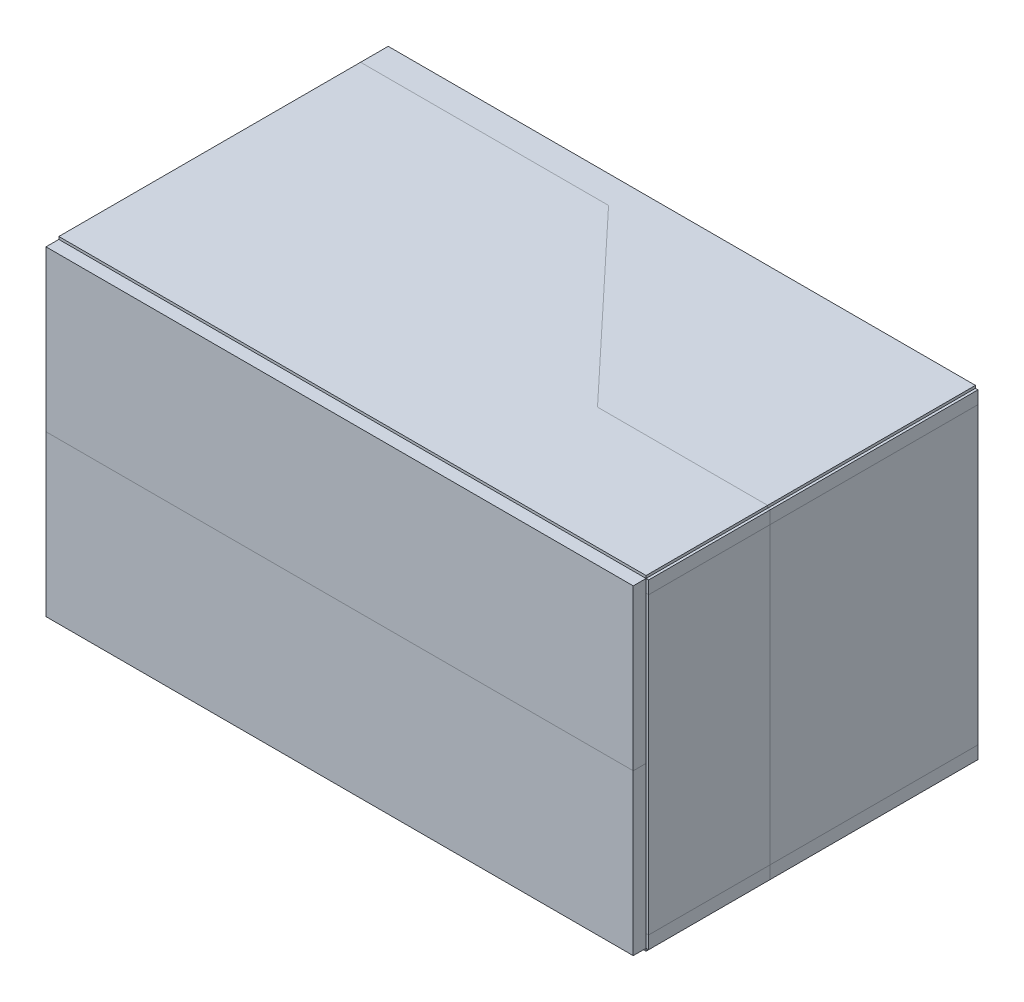
SolidWorks part; units mm, degrees
other "후면"
other "천장2"
other "천장1"
other "좌측면"
other "정면"
other "우측면"
other "바닥"
other "후면하단작음2"
other "후면상단작음2"
other "상단인테리어2"
other "하단인테리어2"
other "후면하단큼1"
other "후면상단큼1"
other "후면하단작음1"
other "후면상단작음1"
other "상단인테리어1"
other "하단인테리어1"
other "TV다이"
other "TV다이문1"
other "TV다이문2"
other "TV다이문3"
other "TV다이문4"
other "TV다이문고리1"
other "TV다이문고리2"
other "TV다이문고리3"
other "TV다이문고리4"
other "게임기1"
other "게임기2"
other "게임기2 버튼1"
other "게임기2 버튼2"
other "게임기2 버튼3"
other "게임기2 버튼4"
other "게임기2 버튼5"
other "게임기2 버튼6"
other "TV"
other "중간테이블"
other "소파"
other "에어컨"
other "카펫"
ref_plane "정면" through (0, 0, 0) normal (0, 0, 1) x (1, 0, 0)
ref_plane "윗면" through (0, 0, 0) normal (0, 1, 0) x (1, 0, 0)
ref_plane "우측면" through (0, 0, 0) normal (1, 0, 0) x (0, 0, -1)
sketch "스케치1" plane through (0, 0, 0) normal (0, 0, 1) x (1, 0, 0)
  line L1 (51, 74.896) -> (280, 74.896)
  line L2 (51, 74.896) -> (51, -50)
  line L3 (51, -50) -> (280, -50)
  line L4 (280, 74.896) -> (280, -50)
extrude "보스-돌출1" add sketch "스케치1" along normal up to surface (7.8606 mm away)
sketch "스케치2" plane through (0, 0, 7.8606) normal (0, 0, 1) x (1, 0, 0)
  line L0 (280, 74.896) -> (280, -50) construction
  line L1 (51, 74.896) -> (280, 74.896)
  line L2 (51, 74.896) -> (51, 69.896)
  line L3 (51, 69.896) -> (280, 69.896)
  line L4 (280, 74.896) -> (280, 69.896)
  dimension "D1" = 5
extrude "컷-돌출1" cut sketch "스케치2" against normal up to surface (7.8606 mm away) contours L1 L3 L2 up to face at (165.5, 12.448, 0)
sketch "스케치4" plane through (0, 0, 7.8606) normal (0, 0, 1) x (1, 0, 0)
  line L0 (280, 69.896) -> (280, -50) construction
  line L1 (51, -50) -> (280, -50)
  line L2 (51, -50) -> (51, -45)
  line L3 (51, -45) -> (280, -45)
  line L4 (280, -50) -> (280, -45)
  line M1 (280, -50) -> (280, 69.896)
  line M3 (51, 69.896) -> (51, -50)
  line M4 (51, -50) -> (280, -50)
  dimension "D1" = 5
extrude "컷-돌출2" cut sketch "스케치4" against normal up to surface (7.8606 mm away) contours L3 M3 M4 M1 up to face at (165.5, 9.948, 0)
sketch "스케치5" plane through (0, 0, 7.8606) normal (0, 0, 1) x (1, 0, 0)
  line L0 (51, -45) -> (280, -45) construction
  line L1 (280, 69.896) -> (275, 69.896)
  line L2 (280, 69.896) -> (280, -45)
  line L3 (280, -45) -> (275, -45)
  line L4 (275, 69.896) -> (275, -45)
  line M1 (51, -45) -> (280, -45)
  line M2 (280, -45) -> (280, 69.896)
  line M3 (280, 69.896) -> (51, 69.896)
  dimension "D1" = 5
extrude "컷-돌출3" cut sketch "스케치5" against normal up to surface (7.8606 mm away) contours L4 M3 M1 M2 up to face at (165.5, 12.448, 0)
sketch "스케치6" plane through (0, 69.896, 0) normal (0, 1, 0) x (1, 0, 0)
  line L1 (51, 0) -> (280, 0)
  line L2 (51, 0) -> (51, -128.4421)
  line L3 (51, -128.4421) -> (280, -128.4421)
  line L4 (280, 0) -> (280, -128.4421)
extrude "보스-돌출3" add sketch "스케치6" along normal blind 5 separate body
sketch "스케치7" plane through (0, 0, 7.8606) normal (0, 0, 1) x (1, 0, 0)
  line L0 (51, -45) -> (275, -45) construction
  line L1 (51, 69.896) -> (56, 69.896)
  line L2 (51, 69.896) -> (51, -45)
  line L3 (51, -45) -> (56, -45)
  line L4 (56, 69.896) -> (56, -45)
  dimension "D1" = 5
extrude "보스-돌출4" add sketch "스케치7" along normal up to surface (120.5815 mm away) separate body up to face at (165.5, 72.396, 128.4421)
sketch "스케치8" plane through (0, -45, 0) normal (0, -1, 0) x (1, 0, 0)
  line L1 (51, 128.4421) -> (280, 128.4421)
  line L2 (51, 128.4421) -> (51, 0)
  line L3 (51, 0) -> (280, 0)
  line L4 (280, 128.4421) -> (280, 0)
extrude "보스-돌출5" add sketch "스케치8" along normal blind 5 separate body
sketch "스케치9" plane through (0, 0, 128.4421) normal (0, 0, 1) x (1, 0, 0)
  line L1 (51, 74.896) -> (280, 74.896)
  line L2 (51, 74.896) -> (51, 12.446)
  line L3 (51, 12.446) -> (280, 12.446)
  line L4 (280, 74.896) -> (280, 12.446)
  dimension "D1" = 62.45
extrude "보스-돌출6" add sketch "스케치9" along normal blind 5 separate body
sketch "스케치10" plane through (0, 0, 128.4421) normal (0, 0, 1) x (1, 0, 0)
  line L1 (51, 12.446) -> (280, 12.446)
  line L2 (51, 12.446) -> (51, -50)
  line L3 (51, -50) -> (280, -50)
  line L4 (280, 12.446) -> (280, -50)
extrude "보스-돌출7" add sketch "스케치10" along normal blind 5 separate body
sketch "스케치11" plane through (275, 0, 0) normal (1, 0, 0) x (0, 0, -1)
  line L1 (0, -45) -> (-128.4421, -45)
  line L2 (0, -45) -> (0, 69.896)
  line L3 (0, 69.896) -> (-128.4421, 69.896)
  line L4 (-128.4421, -45) -> (-128.4421, 69.896)
extrude "보스-돌출8" add sketch "스케치11" along normal blind 5 separate body
sketch "스케치12" plane through (0, -50, 0) normal (0, -1, 0) x (1, 0, 0)
  line L0 (51, 10.7712) -> (147.7059, 10.7712)
  line L1 (51, 128.4421) -> (51, 0) construction
  line L2 (147.7059, 10.7712) -> (213.6585, 81.0356)
  line L3 (213.6585, 81.0356) -> (280, 81.0356)
  line L4 (280, 0) -> (280, 128.4421) construction
  line L5 (51, 10.7712) -> (51, 0)
  line L6 (51, 0) -> (280, 0)
  line L7 (280, 0) -> (280, 81.0356)
extrude "보스-돌출9" add sketch "스케치12" along normal blind 1 separate body
sketch "스케치13" plane through (0, -50, 0) normal (0, -1, 0) x (1, 0, 0)
  line L0 (51, 128.4421) -> (51, 10.7712)
  line L1 (51, 10.7712) -> (147.7059, 10.7712)
  line L2 (147.7059, 10.7712) -> (213.6585, 81.0356)
  line L3 (213.6585, 81.0356) -> (280, 81.0356)
  line L4 (280, 81.0356) -> (280, 128.4421)
  line L5 (280, 128.4421) -> (51, 128.4421)
extrude "보스-돌출10" add sketch "스케치13" along normal blind 1 separate body
sketch "스케치14" plane through (280, 0, 0) normal (1, 0, 0) x (0, 0, -1)
  line L1 (-81.0356, -50) -> (-128.4421, -50)
  line L2 (-81.0356, -50) -> (-81.0356, -45)
  line L3 (-81.0356, -45) -> (-128.4421, -45)
  line L4 (-128.4421, -50) -> (-128.4421, -45)
extrude "보스-돌출11" add sketch "스케치14" along normal blind 1 separate body
sketch "스케치15" plane through (280, 0, 0) normal (1, 0, 0) x (0, 0, -1)
  line L1 (-81.0356, -50) -> (0, -50)
  line L2 (-81.0356, -50) -> (-81.0356, -45)
  line L3 (-81.0356, -45) -> (0, -45)
  line L4 (0, -50) -> (0, -45)
extrude "보스-돌출12" add sketch "스케치15" along normal blind 1 separate body
sketch "스케치16" plane through (280, 0, 0) normal (1, 0, 0) x (0, 0, -1)
  line L0 (-128.4421, 69.896) -> (0, 69.896) construction
  line L1 (-128.4421, -45) -> (-81.0356, -45)
  line L2 (-128.4421, -45) -> (-128.4421, 69.896)
  line L3 (-128.4421, 69.896) -> (-81.0356, 69.896)
  line L4 (-81.0356, -45) -> (-81.0356, 69.896)
extrude "보스-돌출13" add sketch "스케치16" along normal blind 1 separate body
sketch "스케치17" plane through (280, 0, 0) normal (1, 0, 0) x (0, 0, -1)
  line L0 (0, 74.896) -> (0, 69.896) construction
  line L1 (-81.0356, -45) -> (0, -45)
  line L2 (-81.0356, -45) -> (-81.0356, 69.896)
  line L3 (-81.0356, 69.896) -> (0, 69.896)
  line L4 (0, -45) -> (0, 69.896)
  line L5 (-128.4421, 69.896) -> (0, 69.896) construction
extrude "보스-돌출14" add sketch "스케치17" along normal blind 1 separate body
ref_plane "평면1" through (0, 12.446, 0) normal (0, 1, 0) x (1, 0, 0)
mirror "대칭 복사2" about plane through (0, 12.446, 0) normal (0, 1, 0) of bodies 112 113 114 115
other "바디 저장1"
other "바디 저장2"
sketch "스케치18" plane through (0, 0, 7.8606) normal (0, 0, 1) x (1, 0, 0)
  line L0 (51, 69.896) -> (280, 69.896) construction
  line L1 (105.5, 69.896) -> (225.5, 69.896)
  line L2 (105.5, 69.896) -> (105.5, 49.896)
  line L3 (105.5, 49.896) -> (225.5, 49.896)
  line L4 (225.5, 69.896) -> (225.5, 49.896)
  line L5 (56, 69.896) -> (56, -45) construction
  dimension "D1" = 120
  dimension "D2" = 49.5
  dimension "D3" = 20
extrude "보스-돌출15" add sketch "스케치18" along normal blind 30 separate body
sketch "스케치19" plane through (0, 49.896, 0) normal (0, -1, 0) x (1, 0, 0)
  line L0 (105.5, 37.8606) -> (105.5, 7.8606) construction
  line L1 (105.5, 32.8606) -> (225.5, 32.8606)
  line L2 (105.5, 32.8606) -> (105.5, 12.8606)
  line L3 (105.5, 12.8606) -> (225.5, 12.8606)
  line L4 (225.5, 32.8606) -> (225.5, 12.8606)
  line L5 (225.5, 37.8606) -> (225.5, 7.8606) construction
  line L6 (105.5, 37.8606) -> (225.5, 37.8606) construction
  dimension "D1" = 5
  dimension "D2" = 20
extrude "컷-돌출4" cut sketch "스케치19" against normal blind 2
sketch "스케치20" plane through (0, 51.896, 0) normal (0, -1, 0) x (1, 0, 0)
  line L1 (105.5, 12.8606) -> (225.5, 12.8606) construction
  line L2 (105.5, 32.8606) -> (134.75, 32.8606)
  line L3 (105.5, 32.8606) -> (105.5, 12.8606)
  line L4 (105.5, 12.8606) -> (134.75, 12.8606)
  line L5 (134.75, 32.8606) -> (134.75, 12.8606)
  dimension "D1" = 29.25
extrude "보스-돌출16" add sketch "스케치20" along normal blind 2 separate body
pattern_linear "선형 패턴1" count 4 spacing 30.25 along (1, 0, 0) of bodies 160
sketch "스케치21" plane through (0, 49.896, 0) normal (0, -1, 0) x (1, 0, 0)
  line L0 (134.75, 32.8606) -> (105.5, 32.8606) construction
  line L1 (134.75, 12.8606) -> (134.75, 32.8606) construction
  line L2 (134.75, 32.8606) -> (135.75, 32.8606) construction
  line L3 (135.25, 32.8606) -> (135.25, 12.8606) construction
  line L4 (105.5, 12.8606) -> (225.5, 12.8606) construction
  line L5 (165, 32.8606) -> (166, 32.8606) construction
  line L6 (165.5, 32.8606) -> (165.5, 12.8606) construction
  line L7 (105.5, 12.8606) -> (225.5, 12.8606) construction
  line L8 (195.75, 32.8606) -> (195.75, 12.8606) construction
  line L9 (196.25, 32.8606) -> (195.25, 32.8606) construction
  circle A0 centre (131.75, 22.8606) radius 1
  circle A1 centre (138.75, 22.8606) radius 1
  circle A2 centre (192.25, 22.8606) radius 1
  circle A3 centre (199.25, 22.8606) radius 1
  dimension "D1" = 2
  dimension "D2" = 10
  dimension "D3" = 3
extrude "보스-돌출18" add sketch "스케치21" along normal blind 1 separate body
sketch "스케치23" plane through (0, 0, 37.8606) normal (0, 0, 1) x (1, 0, 0)
  line L0 (225.5, 69.896) -> (105.5, 69.896) construction
  line L1 (108.2391, 50.896) -> (114.2391, 50.896)
  line L2 (108.2391, 50.896) -> (108.2391, 65.896)
  line L3 (108.2391, 65.896) -> (114.2391, 65.896)
  line L4 (114.2391, 50.896) -> (114.2391, 65.896)
  dimension "D1" = 6
  dimension "D2" = 15
  dimension "D3" = 4
extrude "보스-돌출19" add sketch "스케치23" along normal blind 15 separate body
sketch "스케치24" plane through (0, 50.896, 0) normal (0, -1, 0) x (1, 0, 0)
  line L0 (108.2391, 52.8606) -> (114.2391, 52.8606) construction
  line L1 (108.7391, 52.8606) -> (113.7391, 52.8606)
  line L2 (108.7391, 52.8606) -> (108.7391, 37.8606)
  line L3 (108.7391, 37.8606) -> (113.7391, 37.8606)
  line L4 (113.7391, 52.8606) -> (113.7391, 37.8606)
  line L5 (108.2391, 37.8606) -> (114.2391, 37.8606) construction
  line L6 (108.2391, 52.8606) -> (108.2391, 37.8606) construction
  dimension "D1" = 5
  dimension "D2" = 0.5
extrude "컷-돌출5" cut sketch "스케치24" against normal blind 2
sketch "스케치25" plane through (0, 0, 52.8606) normal (0, 0, 1) x (1, 0, 0)
  line L0 (114.2391, 65.896) -> (108.2391, 65.896) construction
  line L1 (108.7391, 52.896) -> (113.7391, 52.896)
  line L2 (108.7391, 52.896) -> (108.7391, 64.896)
  line L3 (108.7391, 64.896) -> (113.7391, 64.896)
  line L4 (113.7391, 52.896) -> (113.7391, 64.896)
  dimension "D1" = 1
extrude "컷-돌출6" cut sketch "스케치25" against normal blind 2
sketch "스케치27" plane through (0, 50.896, 0) normal (0, -1, 0) x (1, 0, 0)
  line L9 (108.7391, 52.8606) -> (108.7391, 37.8606)
  line L10 (108.7391, 52.8606) -> (108.7391, 37.8606) construction
  line L11 (108.2391, 37.8606) -> (108.7391, 37.8606) construction
  line L12 (108.7391, 37.8606) -> (111.2391, 37.8606)
  line L13 (111.2391, 37.8606) -> (108.7391, 52.8606)
  dimension "D1" = 2.5
extrude "보스-돌출23" add sketch "스케치27" against normal up to surface (14 mm away) up to face at (111.2391, 64.896, 51.8606)
sketch "스케치28" plane through (0, 50.896, 0) normal (0, -1, 0) x (1, 0, 0)
  line L1 (113.7391, 37.8606) -> (113.7391, 52.8606)
  line L2 (113.7391, 52.8606) -> (114.2391, 52.8606) construction
  line L3 (113.7391, 52.8606) -> (108.7391, 52.8606) construction
  line L5 (113.7391, 37.8606) -> (111.2391, 37.8606)
  line L6 (111.2391, 37.8606) -> (108.7391, 52.8606) construction
  line L7 (111.2391, 37.8606) -> (111.2043, 38.0695)
  line L8 (111.2043, 38.0695) -> (113.7391, 52.8606)
extrude "보스-돌출26" add sketch "스케치28" against normal up to surface (14 mm away) up to face at (111.3224, 64.896, 51.8606)
sketch "스케치29" plane through (0, 50.896, 0) normal (0, -1, 0) x (1, 0, 0)
  line L0 (105.5, 37.8606) -> (225.5, 37.8606) construction
  line L4 (127.0564, 37.8606) -> (145.0564, 37.8606)
  line L5 (124.0564, 40.8606) -> (124.0564, 44.8606)
  line L6 (127.0564, 47.8606) -> (145.0564, 47.8606)
  line L7 (148.0564, 40.8606) -> (148.0564, 44.8606)
  arc A2 (127.0564, 47.8606) -> (124.0564, 44.8606) centre (127.0564, 44.8606) ccw
  arc A3 (127.0564, 37.8606) -> (124.0564, 40.8606) centre (127.0564, 40.8606) cw
  arc A4 (148.0564, 44.8606) -> (145.0564, 47.8606) centre (145.0564, 44.8606) ccw
  arc A5 (148.0564, 40.8606) -> (145.0564, 37.8606) centre (145.0564, 40.8606) cw
  point P8 (124.0564, 47.8606)
  point P11 (124.0564, 37.8606)
  point P14 (148.0564, 47.8606)
  point P17 (148.0564, 37.8606)
  dimension "D3" = 3
  dimension "D4" = 3
  dimension "D5" = 3
  dimension "D6" = 3
  dimension "D1" = 24
  dimension "D2" = 10
extrude "보스-돌출27" add sketch "스케치29" against normal blind 2 separate body contours A5 L7 A4 L6 A2 L5 A3 L4
sketch "스케치30" plane through (0, 50.896, 0) normal (0, -1, 0) x (1, 0, 0)
  line L0 (127.7564, 47.1606) -> (144.3564, 47.1606)
  line L1 (127.0564, 47.8606) -> (145.0564, 47.8606)
  line L2 (127.0564, 47.8606) -> (127.0564, 37.8606)
  line L3 (127.0564, 37.8606) -> (145.0564, 37.8606)
  line L4 (145.0564, 47.8606) -> (145.0564, 37.8606)
  line L5 (144.3564, 47.1606) -> (144.3564, 38.5606)
  line L6 (127.7564, 38.5606) -> (144.3564, 38.5606)
  line L7 (127.7564, 47.1606) -> (127.7564, 38.5606)
  dimension "D1" = 0.7
extrude "컷-돌출7" cut sketch "스케치30" against normal blind 0.1
sketch "스케치31" plane through (0, 50.896, 0) normal (0, -1, 0) x (1, 0, 0)
  circle A0 centre (126.1941, 46.3871) radius 0.35
  circle A1 centre (125.2049, 45.9652) radius 0.35
  circle A2 centre (125.942, 45.3154) radius 0.35
  dimension "D1" = 0.7
  dimension "D2" = 0.7
  dimension "D3" = 0.7
extrude "보스-돌출28" add sketch "스케치31" along normal blind 0.2 separate body
sketch "스케치32" plane through (0, 50.896, 0) normal (0, -1, 0) x (1, 0, 0)
  circle A0 centre (145.7092, 40.6848) radius 0.35
  circle A1 centre (146.6732, 39.8494) radius 0.35
  circle A2 centre (145.7092, 39.3878) radius 0.35
  dimension "D1" = 0.7
  dimension "D2" = 0.7
  dimension "D3" = 0.7
extrude "보스-돌출29" add sketch "스케치32" along normal blind 0.2 separate body
sketch "스케치33" plane through (0, 69.896, 0) normal (0, -1, 0) x (1, 0, 0)
  line L1 (105.7778, 118.4421) -> (230.2222, 118.4421)
  line L2 (105.7778, 118.4421) -> (105.7778, 48.4421)
  line L3 (105.7778, 48.4421) -> (230.2222, 48.4421)
  line L4 (230.2222, 118.4421) -> (230.2222, 48.4421)
  line L5 (56, 128.4421) -> (56, 7.8606) construction
  line L6 (280, 81.0356) -> (280, 128.4421) construction
  line L7 (51, 128.4421) -> (280, 128.4421) construction
  dimension "D1" = 49.7778
  dimension "D2" = 49.7778
  dimension "D3" = 70
  dimension "D4" = 10
extrude "보스-돌출30" add sketch "스케치33" along normal blind 3 separate body
sketch "스케치34" plane through (0, 66.896, 0) normal (0, -1, 0) x (1, 0, 0)
  line L0 (108.7778, 115.4421) -> (108.7778, 51.4421)
  line L1 (108.7778, 51.4421) -> (227.2222, 51.4421)
  line L2 (227.2222, 51.4421) -> (227.2222, 115.4421)
  line L3 (227.2222, 115.4421) -> (108.7778, 115.4421)
  line L4 (105.7778, 118.4421) -> (105.7778, 48.4421)
  line L5 (105.7778, 48.4421) -> (230.2222, 48.4421)
  line L6 (230.2222, 48.4421) -> (230.2222, 118.4421)
  line L7 (230.2222, 118.4421) -> (105.7778, 118.4421)
  line L8 (105.7778, 118.4421) -> (105.7778, 48.4421)
  line L9 (105.7778, 48.4421) -> (230.2222, 48.4421)
  line L10 (230.2222, 48.4421) -> (230.2222, 118.4421)
  line L11 (230.2222, 118.4421) -> (105.7778, 118.4421)
  dimension "D1" = 0
  dimension "D2" = 3
extrude "컷-돌출8" cut sketch "스케치34" against normal blind 1 contours L2 L3 L0 L1
ref_plane "평면4" through (0, 19.896, 0) normal (0, -1, 0) x (-1, 0, 0)
sketch "스케치36" plane through (0, 19.896, 0) normal (0, -1, 0) x (-1, 0, 0)
  line L0 (-123, -22.8606) -> (-213, -22.8606) construction
  line L1 (-123, -37.8606) -> (-213, -37.8606)
  line L2 (-123, -7.8606) -> (-213, -7.8606)
  line L3 (-56, -128.4421) -> (-56, -7.8606) construction
  line L4 (-51, -7.8606) -> (-275, -7.8606) construction
  line L5 (-123, -29.8606) -> (-213, -29.8606)
  line L6 (-123, -15.8606) -> (-213, -15.8606)
  arc A0 (-123, -37.8606) -> (-123, -7.8606) centre (-123, -22.8606) ccw
  arc A1 (-213, -7.8606) -> (-213, -37.8606) centre (-213, -22.8606) ccw
  arc A2 (-213, -15.8606) -> (-213, -29.8606) centre (-213, -22.8606) ccw
  arc A3 (-123, -29.8606) -> (-123, -15.8606) centre (-123, -22.8606) ccw
  point P2 (-168, -22.8606)
  dimension "D1" = 30
  dimension "D2" = 90
  dimension "D3" = 67
  dimension "D4" = 8
extrude "보스-돌출31" add sketch "스케치36" along normal blind 15 and the other way blind 5 separate body
sketch "스케치37" plane through (0, 0, 7.8606) normal (0, 0, 1) x (1, 0, 0)
  line L0 (51, -45) -> (275, -45) construction
  line L1 (93, -45) -> (243, -45)
  line L2 (93, -45) -> (93, -15)
  line L3 (93, -15) -> (243, -15)
  line L4 (243, -45) -> (243, -15)
  line L5 (56, 69.896) -> (56, -45) construction
  dimension "D1" = 150
  dimension "D2" = 37
  dimension "D3" = 30
extrude "보스-돌출32" add sketch "스케치37" along normal blind 50 separate body
sketch "스케치38" plane through (0, 0, 57.8606) normal (0, 0, 1) x (1, 0, 0)
  line L1 (108, -15) -> (228, -15)
  line L2 (108, -15) -> (108, -34.413)
  line L3 (108, -34.413) -> (228, -34.413)
  line L4 (93, -15) -> (93, -45)
  line L5 (93, -45) -> (243, -45)
  line L6 (243, -45) -> (243, -15)
  line L7 (243, -15) -> (93, -15)
  line L8 (93, -15) -> (93, -45)
  line L9 (93, -45) -> (243, -45)
  line L10 (243, -45) -> (243, -15)
  line L11 (243, -15) -> (93, -15)
  line L12 (228, -15) -> (228, -34.413)
  line M8 (243, -15) -> (93, -15)
  dimension "D2" = 120
  dimension "D3" = 15
  dimension "D1" = 0
extrude "컷-돌출9" cut sketch "스케치38" against normal blind 25 contours L12 L2 L3 M8
fillet "필렛1" radius 10 3 edges at (228, -24.7065, 57.8606) (108, -24.7065, 57.8606) (168, -34.413, 57.8606)
sketch "스케치39" plane through (56, 0, 0) normal (1, 0, 0) x (0, 0, -1)
  line L0 (-128.4421, 69.896) -> (-128.4421, -45) construction
  line L1 (-128.4421, -22.558) -> (-108.4421, -22.558)
  line L2 (-128.4421, -22.558) -> (-128.4421, 47.442)
  line L3 (-128.4421, 47.442) -> (-108.4421, 47.442)
  line L4 (-108.4421, -22.558) -> (-108.4421, 47.442)
  line L5 (-81.0356, 69.892) -> (-128.4421, 69.892) construction
  dimension "D1" = 70
  dimension "D2" = 22.45
  dimension "D3" = 20
extrude "보스-돌출33" add sketch "스케치39" along normal blind 20 separate body
fillet "필렛2" radius 11 1 edges at (76, 12.442, 108.4421)
sketch "스케치41" plane through (0, 0, 128.4421) normal (0, 0, 1) x (1, 0, 0)
  line L0 (56, 47.442) -> (56, -22.558) construction
  line L1 (58, 42.442) -> (60, 42.442)
  line L2 (58, 42.442) -> (58, -17.558)
  line L3 (58, -17.558) -> (60, -17.558)
  line L4 (60, 42.442) -> (60, -17.558)
  line L6 (76, 47.442) -> (56, 47.442) construction
  line L7 (62, 42.442) -> (62, -17.558)
  line L8 (62, 42.442) -> (64, 42.442)
  line L9 (64, 42.442) -> (64, -17.558)
  line L10 (62, -17.558) -> (64, -17.558)
  line L11 (66, 42.442) -> (66, -17.558)
  line L12 (66, 42.442) -> (68, 42.442)
  line L13 (68, 42.442) -> (68, -17.558)
  line L14 (66, -17.558) -> (68, -17.558)
  line L15 (70, 42.442) -> (70, -17.558)
  line L16 (70, 42.442) -> (72, 42.442)
  line L17 (72, 42.442) -> (72, -17.558)
  line L18 (70, -17.558) -> (72, -17.558)
  dimension "D1" = 2
  dimension "D2" = 2
  dimension "D3" = 60
  dimension "D4" = 5
  dimension "D5" = 4
extrude "컷-돌출11" cut sketch "스케치41" against normal blind 5
sketch "스케치42" plane through (0, 0, 7.8606) normal (0, 0, 1) x (1, 0, 0)
  line L0 (121.6966, -45) -> (209.3034, -45)
  line L1 (93, -45) -> (243, -45) construction
  line L2 (110.8705, 69.896) -> (220.1295, 69.896)
  line L3 (230.2222, 69.896) -> (105.7778, 69.896) construction
  ellipse E0 centre (165.5, 14.9277) end of major axis (258.4247, 14.9277) minor radius 67.9509 (110.8705, 69.896) -> (121.6966, -45) ccw
  ellipse E1 centre (165.5, 14.9277) end of major axis (258.4247, 14.9277) minor radius 67.9509 (209.3034, -45) -> (220.1295, 69.896) ccw
extrude "보스-돌출34" add sketch "스케치42" along normal blind 0.1 separate body
